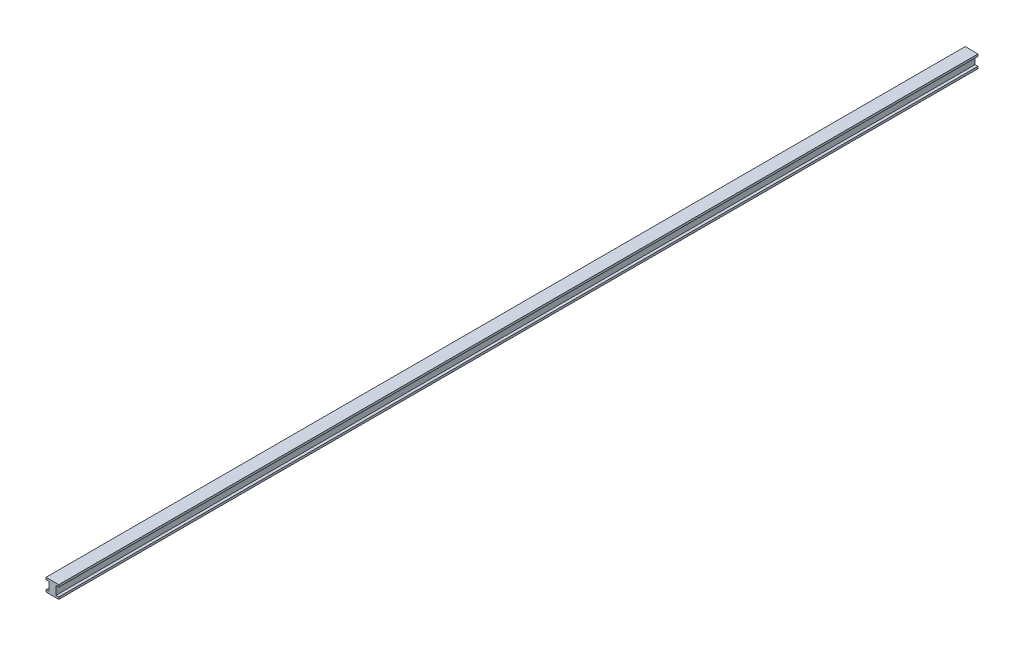
SolidWorks part; units mm, degrees
material "Balsa"
ref_plane "Front Plane" through (0, 0, 0) normal (0, 0, 1) x (1, 0, 0)
ref_plane "Top Plane" through (0, 0, 0) normal (0, 1, 0) x (1, 0, 0)
ref_plane "Right Plane" through (0, 0, 0) normal (1, 0, 0) x (0, 0, -1)
sketch "Sketch1" plane through (0, 0, 0) normal (0, 0, 1) x (1, 0, 0)
  line L0 (0, 0) -> (0, 18.4317) construction
  line L1 (0, 18.4317) -> (0, -26.8921) construction
  line L2 (0, 0) -> (31.0791, 0) construction
  line L3 (31.0791, 0) -> (-34.1871, 0) construction
  line L4 (-5, -6) -> (-5, 6)
  line L5 (-5, 6) -> (-9, 6)
  line L6 (-9, 6) -> (-9, 9)
  line L7 (-9, 9) -> (9, 9)
  line L8 (5, -6) -> (5, 6)
  line L9 (5, 6) -> (9, 6)
  line L10 (9, 6) -> (9, 9)
  line L11 (-5, -6) -> (-9, -6)
  line L12 (9, -6) -> (9, -9)
  line L13 (5, -6) -> (9, -6)
  line L14 (-9, -6) -> (-9, -9)
  line L15 (-9, -9) -> (9, -9)
  point P8 (-5, 0)
  point P15 (0, 9)
  point P20 (5, 0)
  dimension "D1" = 6
  dimension "D2" = 4
  dimension "D3" = 3
  dimension "D4" = 9
extrude "Boss-Extrude1" add sketch "Sketch1" along normal blind 646.904
mirror "Mirror1" about plane through (0, 0, 0) normal (0, 0, -1) of bodies 101
